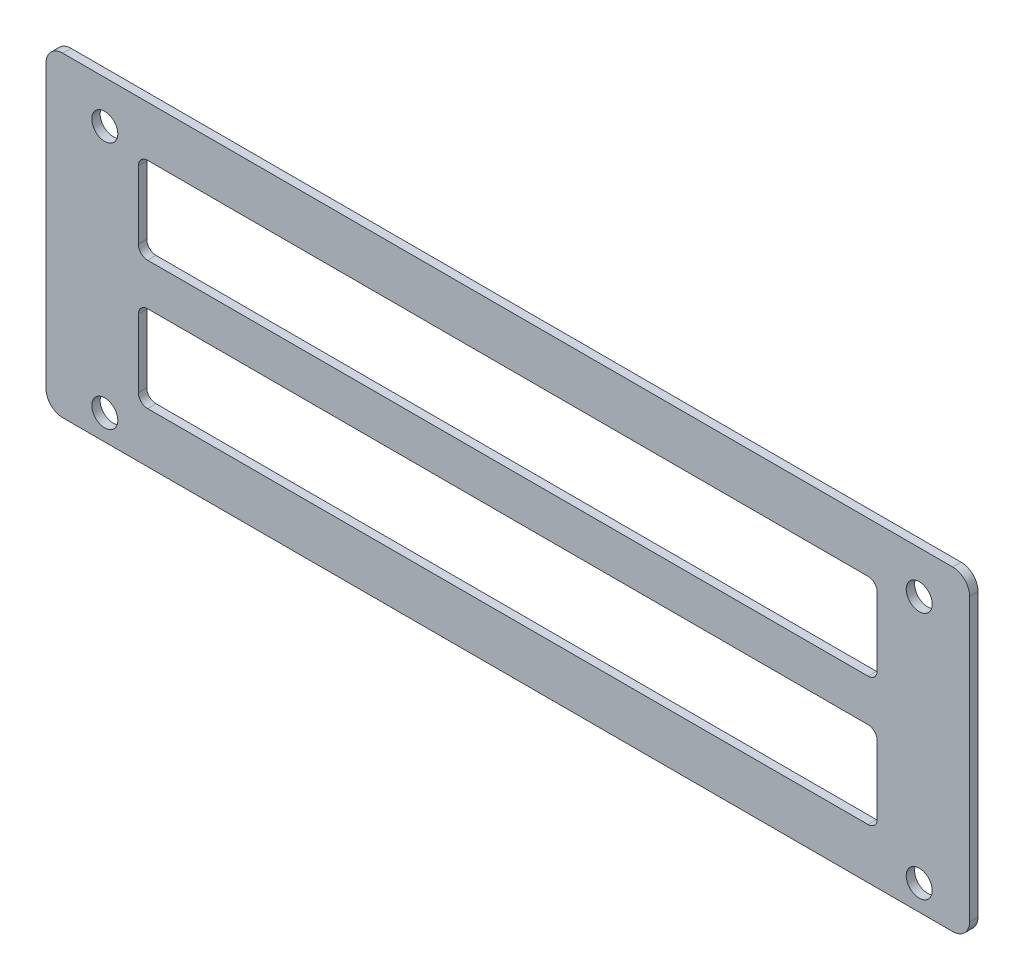
SolidWorks part; units mm, degrees
material "Thornel Mat VMA"
ref_plane "前视基准面" through (0, 0, 0) normal (0, 0, 1) x (1, 0, 0)
ref_plane "上视基准面" through (0, 0, 0) normal (0, 1, 0) x (1, 0, 0)
ref_plane "右视基准面" through (0, 0, 0) normal (1, 0, 0) x (0, 0, -1)
sketch "草图1" plane through (0, 0, 0) normal (0, 0, 1) x (1, 0, 0)
  line L1 (-55, -18.8) -> (55, -18.8)
  line L2 (-55, -18.8) -> (-55, 18.8)
  line L3 (-55, 18.8) -> (55, 18.8)
  line L4 (55, -18.8) -> (55, 18.8)
  line L5 (0, 18.8) -> (0, -18.8) construction
  line L6 (-55, 0) -> (55, 0) construction
  point P0 (0, 0)
  dimension "D1" = 110
  dimension "D2" = 37.6
extrude "凸台-拉伸1" add sketch "草图1" along normal blind 1
sketch "草图2" plane through (0, 0, 0) normal (0, 0, -1) x (-1, 0, 0)
  circle A0 centre (-49, -15.8) radius 1.25 construction
  circle A1 centre (-49, 13.75) radius 1.25 construction
  circle A2 centre (-49, -15.8) radius 1.25 construction
  circle A3 centre (-49, 13.75) radius 1.25 construction
  circle A4 centre (48, -15.8) radius 1.25 construction
  circle A5 centre (48, 13.75) radius 1.25 construction
  circle A6 centre (48, -15.8) radius 1.25 construction
  circle A7 centre (48, 13.75) radius 1.25 construction
  circle A8 centre (48, 13.75) radius 1.55
  circle A9 centre (48, -15.8) radius 1.55
  circle A10 centre (-49, -15.8) radius 1.55
  circle A11 centre (-49, 13.75) radius 1.55
  dimension "D1" = 3.1
extrude "切除-拉伸1" cut sketch "草图2" against normal blind 10
fillet "圆角1" radius 2 4 edges at (-55, -18.8, 0.5) (-55, 18.8, 0.5) (55, -18.8, 0.5) (55, 18.8, 0.5)
sketch "草图3" plane through (0, 0, 0) normal (0, 0, -1) x (-1, 0, 0)
  line L0 (36.4055, 3.2) -> (-17.0945, 3.2) construction
  line L1 (-17.0945, -10.8) -> (36.4055, -10.8) construction
  line L2 (53, -18.8) -> (-53, -18.8) construction
  line L3 (38.4055, 5.2) -> (-19.0945, 5.2)
  line L4 (-19.0945, 5.2) -> (-19.0945, -12.8)
  line L5 (-19.0945, -12.8) -> (38.4055, -12.8)
  line L6 (38.4055, -12.8) -> (38.4055, 5.2)
  line L10 (36.4055, 3.2) -> (6.64, 3.2)
  line L11 (6.64, 3.2) -> (6.64, 0.6)
  line L12 (6.64, 0.6) -> (-9.56, 0.6)
  line L13 (-9.56, 0.6) -> (-9.56, 3.2)
  line L14 (-9.56, 3.2) -> (-13.23, 3.2)
  line L15 (-13.23, 3.2) -> (-13.23, 0.6)
  line L16 (-13.23, 0.6) -> (-17.0945, 0.6)
  line L17 (-17.0945, 0.6) -> (-17.0945, -13.8)
  line L18 (-17.0945, -13.8) -> (36.4055, -13.8)
  line L19 (36.4055, -13.8) -> (36.4055, 3.2)
  line L27 (-17.0945, 3.2) -> (-17.0945, -10.8) construction
  line L29 (36.4055, -10.8) -> (36.4055, 3.2) construction
  dimension "D2" = 8
  dimension "D1" = 0
  dimension "D3" = 2
extrude "切除-拉伸2" cut sketch "草图3" against normal blind 10
sketch "草图4" plane through (0, 0, 0) normal (0, 0, -1) x (-1, 0, 0)
  line L0 (-11.0945, 5.2) -> (-11.0945, -12.8)
  line L1 (38.4055, 5.2) -> (-19.0945, 5.2) construction
  line L2 (-19.0945, -12.8) -> (38.4055, -12.8) construction
  line L3 (-19.0945, 5.2) -> (-19.0945, -12.8) construction
  line L4 (-9.0945, 5.2) -> (-9.0945, -12.8)
  line L5 (-11.0945, -12.8) -> (-9.0945, -12.8)
  line L6 (-11.0945, 5.2) -> (-9.0945, 5.2)
  line L7 (-1.0945, 5.2) -> (0.9055, 5.2)
  line L8 (0.9055, 5.2) -> (0.9055, -12.8)
  line L9 (-1.0945, -12.8) -> (0.9055, -12.8)
  line L10 (-1.0945, 5.2) -> (-1.0945, -12.8)
  line L11 (8.9055, 5.2) -> (10.9055, 5.2)
  line L12 (10.9055, 5.2) -> (10.9055, -12.8)
  line L13 (8.9055, -12.8) -> (10.9055, -12.8)
  line L14 (8.9055, 5.2) -> (8.9055, -12.8)
  line L15 (18.9055, 5.2) -> (20.9055, 5.2)
  line L16 (20.9055, 5.2) -> (20.9055, -12.8)
  line L17 (18.9055, -12.8) -> (20.9055, -12.8)
  line L18 (18.9055, 5.2) -> (18.9055, -12.8)
  line L19 (28.9055, 5.2) -> (30.9055, 5.2)
  line L20 (30.9055, 5.2) -> (30.9055, -12.8)
  line L21 (28.9055, -12.8) -> (30.9055, -12.8)
  line L22 (28.9055, 5.2) -> (28.9055, -12.8)
  line L23 (-11.0945, 5.2) -> (-1.0945, 5.2) construction
  dimension "D1" = 8
  dimension "D2" = 2
  dimension "D4" = 10
  dimension "D3" = 5
extrude "凸台-拉伸2" add sketch "草图4" against normal up to surface (1 mm away) up to face at (-9.6555, -3.8, 1)
fillet "圆角2" radius 1.5 24 edges at (9.0945, 5.2, 0.5) (1.0945, 5.2, 0.5) (1.0945, -12.8, 0.5) (9.0945, -12.8, 0.5) (19.0945, 5.2, 0.5) (11.0945, 5.2, 0.5) (-8.9055, -12.8, 0.5) (-0.9055, -12.8, 0.5) (-0.9055, 5.2, 0.5) (-8.9055, 5.2, 0.5) (-18.9055, -12.8, 0.5) (-10.9055, -12.8, 0.5) (-10.9055, 5.2, 0.5) (-18.9055, 5.2, 0.5) (-28.9055, -12.8, 0.5) (-20.9055, -12.8, 0.5) (-20.9055, 5.2, 0.5) (-28.9055, 5.2, 0.5) (-38.4055, 5.2, 0.5) (-38.4055, -12.8, 0.5) (-30.9055, -12.8, 0.5) (-30.9055, 5.2, 0.5) (19.0945, -12.8, 0.5) (11.0945, -12.8, 0.5)
sketch "草图5" plane through (0, 0, 1) normal (0, 0, 1) x (1, 0, 0)
  line L0 (53, 18.8) -> (-53, 18.8) construction
  line L1 (-44, -12.8) -> (44, -12.8)
  line L2 (-44, -12.8) -> (-44, 12.8)
  line L3 (-44, 12.8) -> (44, 12.8)
  line L4 (44, -12.8) -> (44, 12.8)
  line L5 (0, 12.8) -> (0, -12.8) construction
  line L6 (-44, 0) -> (44, 0) construction
  circle A0 centre (49, 13.75) radius 1.55 construction
  point P0 (0, 0)
  dimension "D1" = 5
  dimension "D2" = 6
extrude "切除-拉伸3" cut sketch "草图5" against normal blind 10
sketch "草图6" plane through (0, 0, 1) normal (0, 0, 1) x (1, 0, 0)
  line L0 (44, -12.8) -> (44, 12.8) construction
  line L1 (-44, -2.5) -> (44, -2.5)
  line L2 (-44, -2.5) -> (-44, 2.5)
  line L3 (-44, 2.5) -> (44, 2.5)
  line L4 (44, -2.5) -> (44, 2.5)
  line L5 (0, 2.5) -> (0, -2.5) construction
  line L6 (-44, 0) -> (44, 0) construction
  point P0 (0, 0)
  dimension "D1" = 5
extrude "凸台-拉伸3" add sketch "草图6" against normal up to surface (1 mm away) up to face at (0, 0, 0)
fillet "圆角3" radius 1.1 8 edges at (-44, 12.8, 0.5) (44, 12.8, 0.5) (44, 2.5, 0.5) (-44, 2.5, 0.5) (44, -2.5, 0.5) (44, -12.8, 0.5) (-44, -2.5, 0.5) (-44, -12.8, 0.5)
